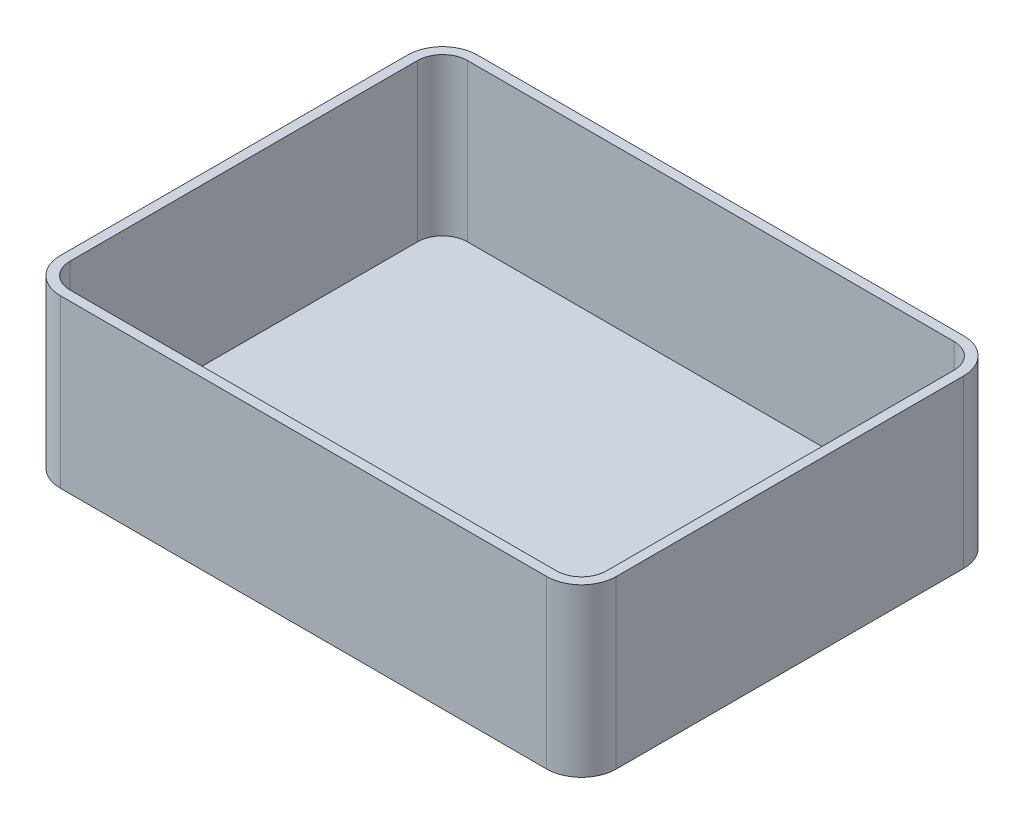
SolidWorks part; units mm, degrees
ref_plane "Front Plane" through (0, 0, 0) normal (0, 0, 1) x (1, 0, 0)
ref_plane "Top Plane" through (0, 0, 0) normal (0, 1, 0) x (1, 0, 0)
ref_plane "Right Plane" through (0, 0, 0) normal (1, 0, 0) x (0, 0, -1)
sketch "Sketch1" plane through (0, 0, 0) normal (0, 1, 0) x (1, 0, 0)
  line L1 (-175, -150) -> (175, -150)
  line L2 (-200, -125) -> (-200, 125)
  line L3 (-175, 150) -> (175, 150)
  line L4 (200, -125) -> (200, 125)
  line L5 (-200, -150) -> (200, 150) construction
  line L6 (-200, 150) -> (200, -150) construction
  arc A0 (175, 150) -> (200, 125) centre (175, 125) cw
  arc A1 (175, -150) -> (200, -125) centre (175, -125) ccw
  arc A2 (-175, -150) -> (-200, -125) centre (-175, -125) cw
  arc A3 (-200, 125) -> (-175, 150) centre (-175, 125) cw
  point P0 (0, 0)
  dimension "D3" = 25
  dimension "D1" = 400
  dimension "D2" = 300
extrude "Boss-Extrude1" add sketch "Sketch1" along normal blind 120
shell "Shell1" thickness 7
